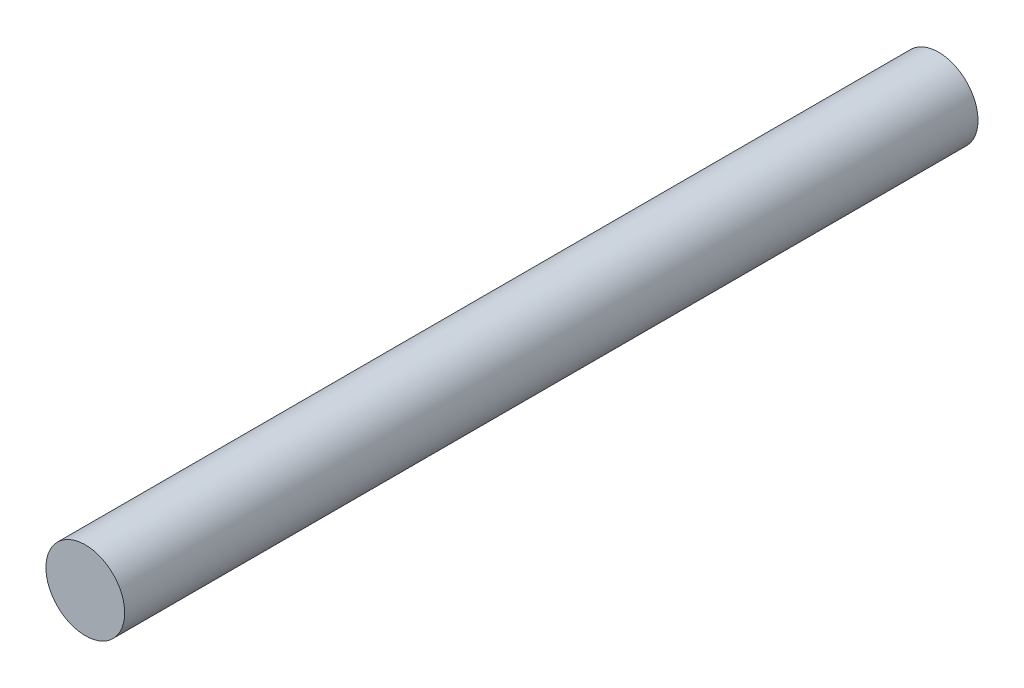
SolidWorks part; units mm, degrees
ref_plane "Plano frontal" through (0, 0, 0) normal (0, 0, 1) x (1, 0, 0)
ref_plane "Plano superior" through (0, 0, 0) normal (0, 1, 0) x (1, 0, 0)
ref_plane "Plano direito" through (0, 0, 0) normal (1, 0, 0) x (0, 0, -1)
sketch "Esboço1" plane through (0, 0, 0) normal (0, 0, 1) x (1, 0, 0)
  circle A0 centre (0, 0) radius 6
  dimension "D1" = 12
extrude "Ressalto-extrusão1" add sketch "Esboço1" along normal blind 130
